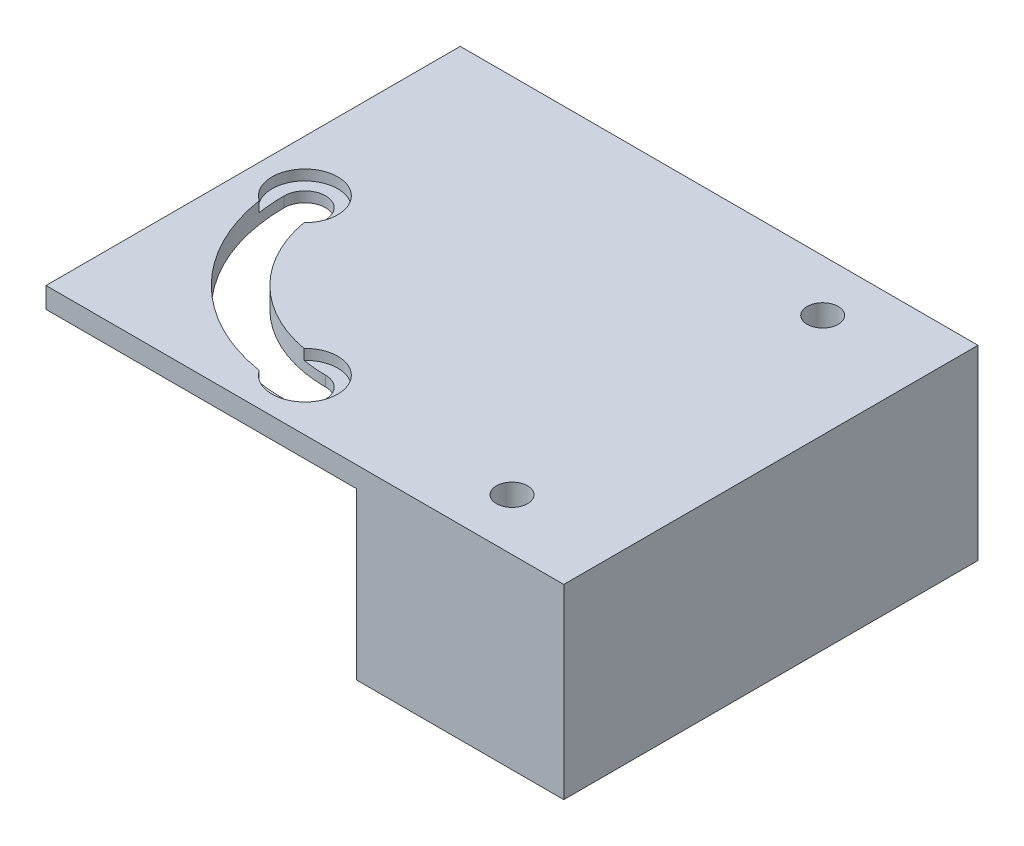
SolidWorks part; units mm, degrees
material "ABS"
ref_plane "Front Plane" through (0, 0, 0) normal (0, 0, 1) x (1, 0, 0)
ref_plane "Top Plane" through (0, 0, 0) normal (0, 1, 0) x (1, 0, 0)
ref_plane "Right Plane" through (0, 0, 0) normal (1, 0, 0) x (0, 0, -1)
sketch "Sketch1" plane through (0, 0, 0) normal (0, 1, 0) x (1, 0, 0)
  line L1 (-30, 20) -> (30, 20)
  line L2 (-30, 20) -> (-30, -20)
  line L3 (-30, -20) -> (30, -20)
  line L4 (30, 20) -> (30, -20)
  line L5 (-30, 20) -> (30, -20) construction
  line L6 (-30, -20) -> (30, 20) construction
  point P0 (0, 0)
  dimension "D1" = 40
  dimension "D2" = 60
extrude "Boss-Extrude1" add sketch "Sketch1" along normal blind 2
sketch "Sketch4" plane through (0, 2, 0) normal (0, 1, 0) x (1, 0, 0)
  line L0 (0, 20) -> (0, -20) construction
  line L1 (30, 20) -> (-30, 20) construction
  line L2 (-30, -20) -> (30, -20) construction
  line L3 (-30, 20) -> (-30, -20) construction
  circle A0 centre (-10, 0) radius 3.5 construction
  arc A1 (-25, 0) -> (-10, -15) centre (-10, 0) ccw construction
  arc A2 (-23, 0) -> (-10, -13) centre (-10, 0) ccw
  arc A3 (-27, 0) -> (-10, -17) centre (-10, 0) ccw
  arc A4 (-27, 0) -> (-23, 0) centre (-25, 0) cw
  arc A5 (-10, -13) -> (-10, -17) centre (-10, -15) cw
  point P6 (-10, 0)
  dimension "D3" = 7
  dimension "D4" = 15
  dimension "D5" = 13
  dimension "D6" = 17
  dimension "D7" = 20
  dimension "D1" = 20
  dimension "D2" = 10
  dimension "D8" = 20
extrude "Cut-Extrude1" cut sketch "Sketch4" against normal blind 14
sketch "Sketch5" plane through (0, 0, 0) normal (0, -1, 0) x (1, 0, 0)
  circle A0 centre (-10, 0) radius 3.5
  dimension "D1" = 7
extrude "Boss-Extrude3" add sketch "Sketch5" along normal blind 16
sketch "Sketch6" plane through (0, 0, 0) normal (0, -1, 0) x (1, 0, 0)
  line L1 (0, 20) -> (30, 20)
  line L2 (0, 20) -> (0, -20)
  line L3 (0, -20) -> (30, -20)
  line L4 (30, 20) -> (30, -20)
extrude "Boss-Extrude4" add sketch "Sketch6" along normal blind 16
sketch "Sketch7" plane through (0, 2, 0) normal (0, 1, 0) x (1, 0, 0)
  line L1 (30, 20) -> (-30, 20) construction
  line L2 (0, 20) -> (0, -20) construction
  line L3 (-30, -20) -> (30, -20) construction
  point P0 (10, 15)
  point P3 (10, -15)
  dimension "D1" = 30
  dimension "D3" = 5
  dimension "D4" = 10
  dimension "D5" = 10
  dimension "D6" = 5
sketch "Sketch8" plane through (0, 2, 0) normal (0, 1, 0) x (1, 0, 0)
  circle A0 centre (-25, 0) radius 3.175
  circle A1 centre (-10, -15) radius 3.175
  dimension "D1" = 6.35
  dimension "D2" = 6.35
extrude "Cut-Extrude2" cut sketch "Sketch8" against normal blind 1
sketch "Sketch9" plane through (0, 2, 0) normal (0, 1, 0) x (1, 0, 0)
  line L0 (-30, -20) -> (30, -20) construction
  line L1 (30, 20) -> (20, 20)
  line L2 (30, 20) -> (30, -20)
  line L3 (30, -20) -> (20, -20)
  line L4 (20, 20) -> (20, -20)
  dimension "D1" = 10
extrude "Cut-Extrude3" cut sketch "Sketch9" against normal blind 20
hole_wizard "Ø3.0mm Dowel Hole1" positions "Sketch10" profile "Sketch12" hole size "Ø3.0" standard "ANSI Metric" end condition through all
sketch "Sketch10" plane through (0, 2, 0) normal (0, 1, 0) x (1, 0, 0)
  point P0 (10, 15)
  point P3 (10, -15)
sketch "Sketch12" plane through (10, 2, -15) normal (1, 0, 0) x (0, 0, 1)
  line L0 (0, 0) -> (0, 18)
  line L1 (0, 18) -> (1.5, 18)
  line L2 (1.5, 18) -> (1.5, 0)
  line L5 (1.5, 0) -> (0, 0)
  line L11 (0, -6.35) -> (0, 107.95) construction
  dimension "Thru Hole Dia." = 3
  dimension "Thru Hole Depth" = 18
